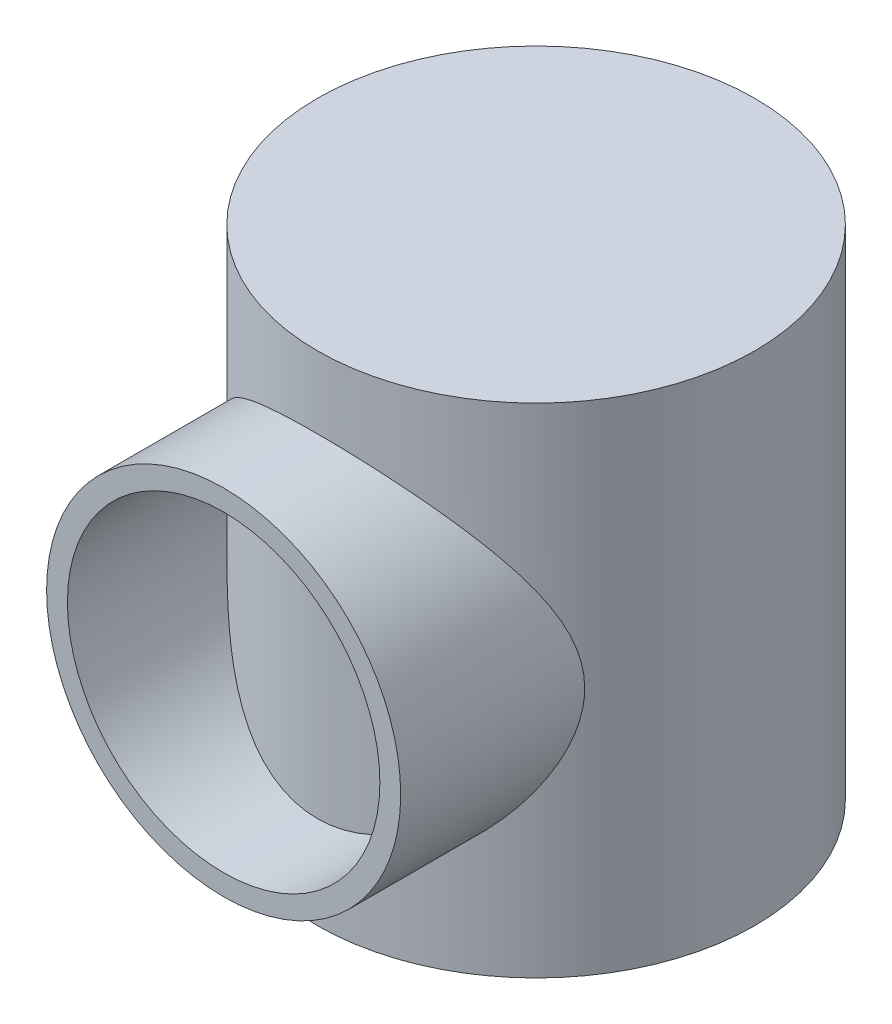
SolidWorks part; units mm, degrees
material "ABS"
ref_plane "Front Plane" through (0, 0, 0) normal (0, 0, 1) x (1, 0, 0)
ref_plane "Top Plane" through (0, 0, 0) normal (0, 1, 0) x (1, 0, 0)
ref_plane "Right Plane" through (0, 0, 0) normal (1, 0, 0) x (0, 0, -1)
sketch "Sketch1" plane through (0, 0, 0) normal (0, 1, 0) x (1, 0, 0)
  circle A0 centre (0, 0) radius 21
  dimension "D1" = 42
extrude "Boss-Extrude1" add sketch "Sketch1" along normal blind 47.8
ref_plane "Plane1" through (0, 0, 30) normal (0, 0, 1) x (1, 0, 0)
sketch "Sketch3" plane through (0, 0, 30) normal (0, 0, 1) x (1, 0, 0)
  line L0 (0, 0) -> (0, 47.8) construction
  line L1 (-21, 0) -> (21, 0) construction
  line L2 (21, 47.8) -> (-21, 47.8) construction
  circle A0 centre (0, 23.9) radius 15
  circle A1 centre (0, 23.9) radius 17
  dimension "D1" = 30
  dimension "D2" = 2
extrude "Boss-Extrude2" add sketch "Sketch3" against normal up to surface (15.3031 mm away)
